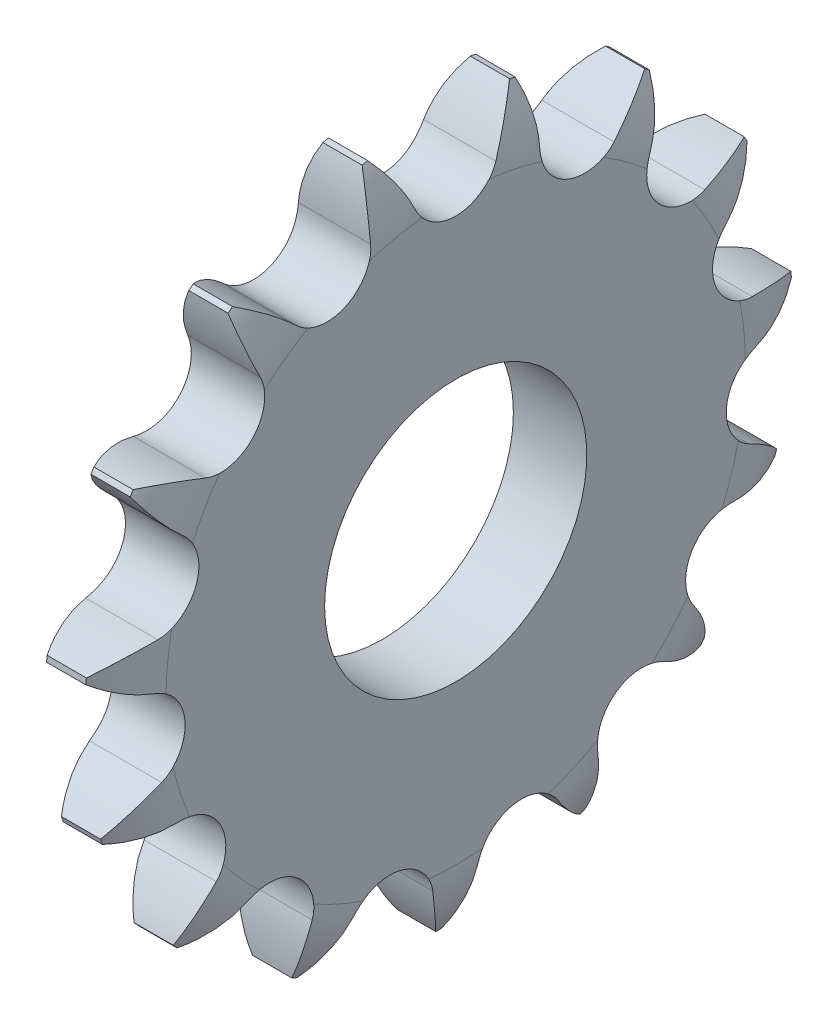
SolidWorks part; units mm, degrees
ref_plane "Plane1" through (0, 0, 0) normal (0, 0, 1) x (1, 0, 0)
ref_plane "Plane2" through (0, 0, 0) normal (0, 1, 0) x (1, 0, 0)
ref_plane "Plane3" through (0, 0, 0) normal (1, 0, 0) x (0, 0, -1)
sketch "Clipboard" plane through (0, 0, 0) normal (0, 1, 0) x (1, 0, 0)
  line L0 (0, 0) -> (9.2004, -2.4653)
  line L1 (-15, 0) -> (100, 0) construction
  line L2 (0, 0) -> (-0.8203, 0.9272)
  line L3 (0, 0) -> (-8.8973, 3.4006)
  line L4 (0, 0) -> (2.9944, 0.8023)
  line L5 (0, 0) -> (-46.8476, -17.4728)
  line L6 (0, 0) -> (-4.4098, -2.9753)
  line L7 (-0.8203, 0.9272) -> (47.2432, 14.7092)
  line L8 (-76.2, 38.1) -> (-73.4, 38.1)
  line L9 (-73.3242, 40.7328) -> (-72.926, 40.7699)
  line L10 (-73.4529, 9.1872) -> (-63.2129, 9.1872)
  circle A0 centre (0, 0) radius 3.175
  circle A1 centre (0, 0) radius 17.7306
  circle A2 centre (0, 0) radius 37.5
  dimension "Dr" = 6.35
  dimension "MHD" = 35.4612
  dimension "Hub_dia" = 75
  dimension "Num_teeth" = 15
  dimension "Pitch" = 9.525
  dimension "Width" = 3.1
  dimension "Side_relief" = 1.238
  dimension "Side_radius" = 9.525
  dimension "Overall_len" = 50
  dimension "Show_teeth" = 15
  dimension "Thickness" = 5.3196
  dimension "OAL" = 50.0005
  dimension "T_dim" = 2.8
  dimension "Fillet_rad" = 0.4
  dimension "Face_width" = 5.32
  dimension "Num_strands" = 1
  dimension "Transv_pitch" = 10.24
  dimension "Plate_wid" = 8.26
sketch "BasProSke" plane through (0, 0, 0) normal (0, 1, 0) x (1, 0, 0)
  line L0 (-10, 0) -> (60, 0) construction
  line L1 (0, 0) -> (0, 20.9886)
  line L2 (0, 0) -> (5.3196, 0)
  line L3 (5.3196, 0) -> (5.3196, 20.9886)
  line L4 (4.0816, 25.6845) -> (1.238, 25.6845)
  arc A0 (0, 20.9886) -> (1.238, 25.6845) centre (9.525, 20.9886) cw
  arc A1 (5.3196, 20.9886) -> (4.0816, 25.6845) centre (-4.2054, 20.9886) ccw
  dimension "Thickness" = 5.3196
  dimension "D1" = 9.525
  dimension "G1" = 1.238
  dimension "G2" = 1.238
  dimension "Diameter" = 51.369
revolve "Base-Revolve" add sketch "BasProSke" angle 360 about L0
sketch "TooCutSke" plane through (0, 0, 0) normal (1, 0, 0) x (0, 0, -1)
  line L0 (0, 22.9381) -> (2.9518, 21.6851) construction
  line L1 (0, 0) -> (0, 107) construction
  line L2 (0, 22.9381) -> (-10, 22.9381) construction
  line L3 (0, 22.9381) -> (-2.9518, 21.6851) construction
  arc A0 (2.9518, 21.6851) -> (5.5304, 25.5938) centre (14.876, 16.6236) cw
  arc A1 (2.9518, 21.6851) -> (-2.9518, 21.6851) centre (0, 22.9381) cw
  arc A2 (-2.9518, 21.6851) -> (-5.5304, 25.5938) centre (-14.876, 16.6236) ccw
  arc A3 (5.5304, 25.5938) -> (-5.5304, 25.5938) centre (0, 0) ccw
  dimension "R1" = 3.2067
  dimension "R2" = 12.954
  dimension "Overcut" = 26.1845
  dimension "Seat_radius" = 22.9381
  dimension "X" = 134
extrude "ToothCut" cut sketch "TooCutSke" along normal through all
pattern_circular "TeethCuts" count 15 every 24 about axis through (-10, 0, 0) along (1, 0, 0) of "ToothCut"
sketch "HubNeaOneSke" plane through (0, 0, 0) normal (-1, 0, 0) x (0, 0, 1)
  circle A0 centre (0, 0) radius 17.7306
  dimension "Diameter" = 35.4612
extrude "HubNearOne" [suppressed] add sketch "HubNeaOneSke" along normal blind 44.6809
fillet "HubNearOneFillet" [suppressed] radius 0.4
sketch "HubNeaBotSke" plane through (0, 0, 0) normal (-1, 0, 0) x (0, 0, 1)
  circle A0 centre (0, 0) radius 17.7306
  dimension "Diameter" = 35.4612
extrude "HubNearBoth" [suppressed] add sketch "HubNeaBotSke" along normal blind 22.3405
fillet "HubNearBothFillet" [suppressed] radius 0.4
ref_plane "FarPln" through (5.3196, 0, 0) normal (1, 0, 0) x (0, 0, -1)
sketch "HubFarSke" plane through (5.3196, 0, 0) normal (1, 0, 0) x (0, 0, -1)
  circle A0 centre (0, 0) radius 17.7306
  dimension "Diameter" = 35.4612
extrude "HubFar" [suppressed] add sketch "HubFarSke" along normal blind 22.3405
fillet "HubFarFillet" [suppressed] radius 0.4
sketch "BorSke" plane through (0, 0, 0) normal (1, 0, 0) x (0, 0, -1)
  circle A0 centre (0, 0) radius 9.5
  dimension "Diameter" = 19
extrude "Bore" cut sketch "BorSke" along normal mid plane 100.001
sketch "KeySke" plane through (0, 0, 0) normal (1, 0, 0) x (0, 0, -1)
  line L0 (-3, 0) -> (-3, 12.3)
  line L1 (-3, 12.3) -> (3, 12.3)
  line L2 (3, 12.3) -> (3, 0)
  line L3 (0, 0) -> (0, 34) construction
  line L4 (-3, 0) -> (3, 0)
  dimension "Offset" = 12.3
  dimension "Width" = 6
extrude "Keyway" [suppressed] cut sketch "KeySke" along normal mid plane 100.001
pattern_circular "Keyway2" [suppressed] count 2 every 90 about axis through (-10, 0, 0) along (1, 0, 0)
equation "' \"Pitch@Clipboard\" = 12.7"
equation "' \"Num_strands@Clipboard\" = 1"
equation "' \"Num_teeth@Clipboard\" = 9"
equation "' \"Hub_dia@Clipboard\" = 50"
equation "' \"Overall_len@Clipboard\" = 3"
equation "' \"Diameter@BorSke\" = 12"
equation "' \"T_dim@Clipboard\" = 1"
equation "' \"Width@KeySke\" = 2"
equation "' \"Dr@Clipboard\" = 8.51"
equation "' \"Face_width@Clipboard\" = 7.2"
equation "' \"Side_radius@Clipboard\" = 12.7"
equation "' \"Side_relief@Clipboard\" = 1.27"
equation "' \"Transv_pitch@Clipboard\" = 13.92"
equation "' \"Show_teeth@Clipboard\" = 9"
equation "' \"Fillet_rad@Clipboard\" = 0.6"
equation "' \"Plate_wid@Clipboard\" = 11.8"
equation "\"Num_teeth@Clipboard\" = int( \"Num_teeth@Clipboard\" )"
equation "\"Num_teeth@Clipboard\" = ((sgn( \"Num_teeth@Clipboard\" - 5.0)+1)*( \"Num_teeth@Clipboard\" - 5.0))/2 +5.0"
equation "\"Num_teeth@Clipboard\" = ((sgn( \"Num_teeth@Clipboard\" - 200.0)-1)*( \"Num_teeth@Clipboard\" - 200.0))/-2 +200.0"
equation "\"MHD@Clipboard\" = \"Pitch@Clipboard\" * (1.0 / tan(3.14159265 / \"Num_teeth@Clipboard\" )) - 1.04 * \"Plate_wid@Clipboard\" - 0.76"
equation "\"Thickness@Clipboard\"  = \"Face_width@Clipboard\" + (\"Num_strands@Clipboard\" - 1) * \"Transv_pitch@Clipboard\""
equation "\"OAL@Clipboard\" = \"Thickness@Clipboard\" + 2 * \"Fillet_rad@Clipboard\" + 1"
equation "\"MHD@Clipboard\" = ((sgn( \"MHD@Clipboard\" - \"Hub_dia@Clipboard\" )-1)*( \"MHD@Clipboard\" - \"Hub_dia@Clipboard\" ))/-2+ \"Hub_dia@Clipboard\""
equation "\"OAL@Clipboard\" = ((sgn( \"OAL@Clipboard\" - \"Overall_len@Clipboard\" )+1)*( \"OAL@Clipboard\" - \"Overall_len@Clipboard\" ))/2 + \"Overall_len@Clipboard\" + 0.0005"
equation "\"Num_teeth@TeethCuts\" = int( \"Show_teeth@Clipboard\" ) + 1"
equation "\"Num_teeth@TeethCuts\" = ((sgn( \"Num_teeth@TeethCuts\" - \"Num_teeth@Clipboard\" )-1)*( \"Num_teeth@TeethCuts\" - \"Num_teeth@Clipboard\" ))/-2+ \"Num_teeth@Clipboard\""
equation "\"Num_teeth@TeethCuts\" = ((sgn( \"Num_teeth@TeethCuts\" - 2.0)+1)*( \"Num_teeth@TeethCuts\" - 2.0))/2 +2.0"
equation "\"Angle@TeethCuts\" = 360.0 / \"Num_teeth@Clipboard\""
equation "\"Seat_radius@TooCutSke\" = ( \"Pitch@Clipboard\" / 2.0) / sin(3.14159265 / \"Num_teeth@Clipboard\" ) - \"Dr@Clipboard\" / 2.0 + \"Dr@Clipboard\" * 0.505"
equation "\"R1@TooCutSke\"  = \"Dr@Clipboard\" * 0.505"
equation "\"X@TooCutSke\" = 140.0 - (90.0 / \"Num_teeth@Clipboard\")"
equation "\"R2@TooCutSke\" = 0.12 * \"Dr@Clipboard\" * ( \"Num_teeth@Clipboard\" + 2.0)"
equation "\"Overcut@TooCutSke\" = 0.5 + 0.625 * \"Pitch@Clipboard\" - 0.5 * \"Dr@Clipboard\"  +  \"Pitch@Clipboard\" / 2.0 / sin(3.14159265 / \"Num_teeth@Clipboard\" )"
equation "\"Diameter@BasProSke\" = 2.0 * ( 0.625 * \"Pitch@Clipboard\" - 0.5 * \"Dr@Clipboard\"  +  \"Pitch@Clipboard\" / 2.0 / sin(3.14159265 / \"Num_teeth@Clipboard\" ))"
equation "\"Thickness@BasProSke\"  = \"Thickness@Clipboard\""
equation "\"G1@BasProSke\" =  \"Side_relief@Clipboard\""
equation "\"G2@BasProSke\" =  \"Side_relief@Clipboard\""
equation "\"D1@BasProSke\" =  \"Side_radius@Clipboard\""
equation "\"Diameter@HubNeaOneSke\" = \"MHD@Clipboard\""
equation "\"Length@HubNearOne\" = \"OAL@Clipboard\" - \"Thickness@BasProSke\""
equation "\"Diameter@HubNeaBotSke\" = \"MHD@Clipboard\""
equation "\"Length@HubNearBoth\" = ( \"OAL@Clipboard\" - \"Thickness@BasProSke\" ) / 2.0"
equation "\"D1@HubNearOneFillet\" = \"Fillet_rad@Clipboard\""
equation "\"D1@HubNearBothFillet\" = \"Fillet_rad@Clipboard\""
equation "\"Thickness@FarPln\" = \"Thickness@BasProSke\""
equation "\"Diameter@HubFarSke\" = \"MHD@Clipboard\""
equation "\"Length@HubFar\" = ( \"OAL@Clipboard\" - \"Thickness@BasProSke\" ) / 2.0"
equation "\"D1@HubFarFillet\" = \"Fillet_rad@Clipboard\""
equation "\"D1@Bore\" = \"OAL@Clipboard\" * 2.0"
equation "\"D1@Keyway\" = \"OAL@Clipboard\" * 2.0"
equation "\"Offset@KeySke\" = \"T_dim@Clipboard\" + \"Diameter@BorSke\" / 2.0"
